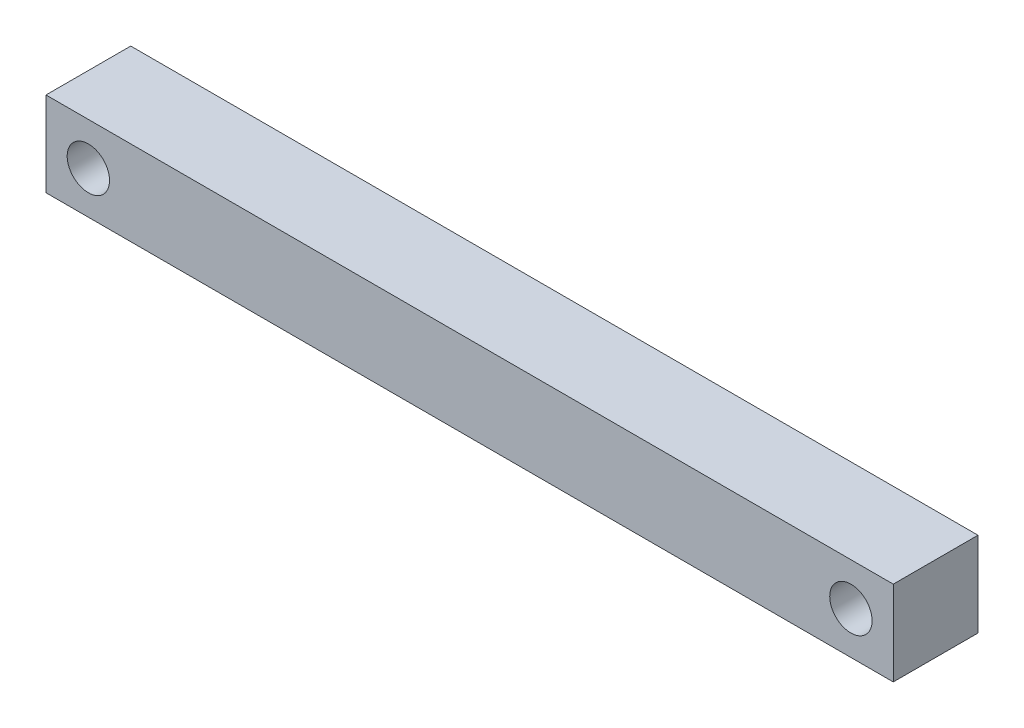
SolidWorks part; units mm, degrees
ref_plane "Front Plane" through (0, 0, 0) normal (0, 0, 1) x (1, 0, 0)
ref_plane "Top Plane" through (0, 0, 0) normal (0, 1, 0) x (1, 0, 0)
ref_plane "Right Plane" through (0, 0, 0) normal (1, 0, 0) x (0, 0, -1)
sketch "Sketch1" plane through (0, 0, 0) normal (0, 0, 1) x (1, 0, 0)
  line L1 (-100, 10) -> (100, 10)
  line L2 (-100, 10) -> (-100, -10)
  line L3 (-100, -10) -> (100, -10)
  line L4 (100, 10) -> (100, -10)
  line L5 (-100, 10) -> (100, -10) construction
  line L6 (-100, -10) -> (100, 10) construction
  point P0 (0, 0)
  dimension "D1" = 200
  dimension "D2" = 20
extrude "Boss-Extrude2" add sketch "Sketch1" along normal blind 20
sketch "Sketch3" plane through (0, 0, 20) normal (0, 0, 1) x (1, 0, 0)
  line L0 (-100, 10) -> (-100, -10) construction
  line L1 (-100, -10) -> (100, -10) construction
  circle A0 centre (-90, 0) radius 5
  dimension "D1" = 10
  dimension "D2" = 10
  dimension "D3" = 10
extrude "Cut-Extrude1" cut sketch "Sketch3" against normal through all
mirror "Mirror1" about plane through (0, 0, 0) normal (1, 0, 0) of "Cut-Extrude1"
equation "\"segment width\" = 60"
equation "\"segment support width\"= 20"
equation "\"servo hole\"= 10'arbitrary atm"
equation "\"segment length 1\"= 200"
equation "\"segment length 2\"= 200"
equation "\"segment length 3\"= 200"
equation "\"segment length 4\"= 100"
equation "\"segment length 5\"= 100"
equation "\"base diameter\"= 100"
equation "\"base height\"= 50"
equation "\"D1@Sketch1\"=\"segment length 1\""
equation "\"D2@Sketch1\"=\"segment support width\""
equation "\"D1@Boss-Extrude2\"=\"segment support width\""
equation "\"D1@Sketch3\"=\"servo hole\""
equation "\"D2@Sketch3\"=\"segment support width\"/2"
equation "\"D3@Sketch3\"=\"segment support width\"/2"
